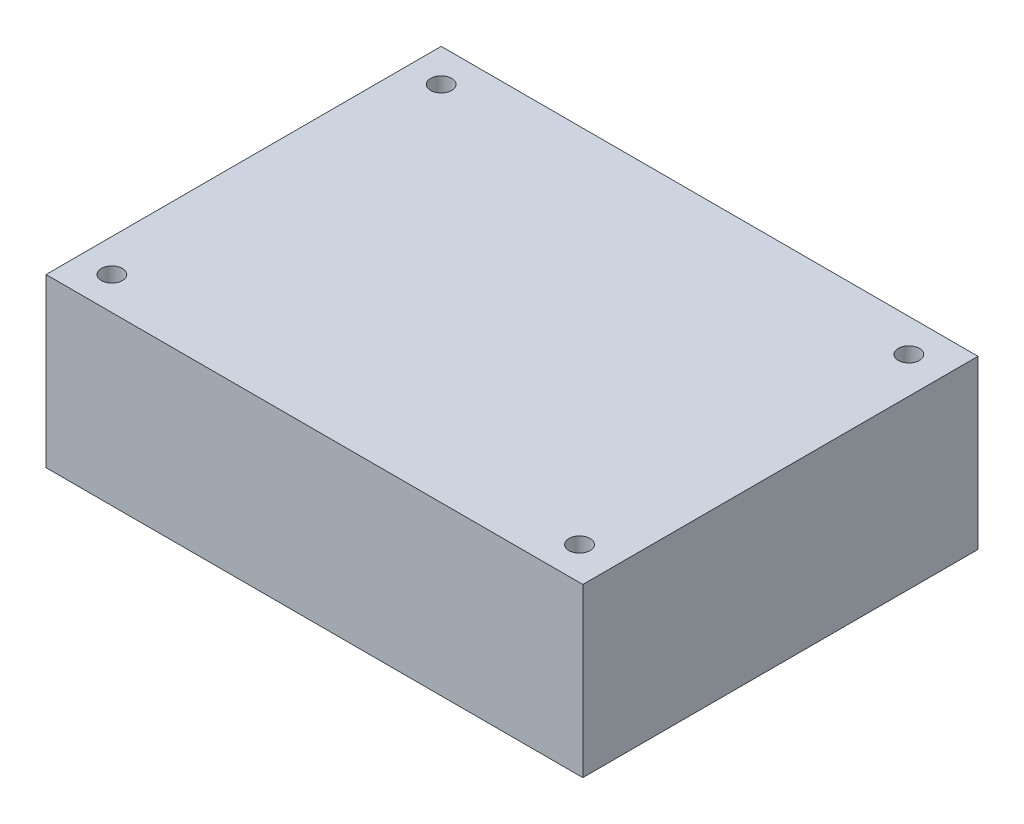
SolidWorks part; units mm, degrees
material "Default"
ref_plane "Front Plane" through (0, 0, 0) normal (0, 0, 1) x (1, 0, 0)
ref_plane "Top Plane" through (0, 0, 0) normal (0, 1, 0) x (1, 0, 0)
ref_plane "Right Plane" through (0, 0, 0) normal (1, 0, 0) x (0, 0, -1)
sketch "Sketch1" plane through (0, 0, 0) normal (0, 1, 0) x (1, 0, 0)
  line L1 (-40.75, 29.9999) -> (40.75, 29.9999)
  line L2 (-40.75, 29.9999) -> (-40.75, -29.9999)
  line L3 (-40.75, -29.9999) -> (40.75, -29.9999)
  line L4 (40.75, 29.9999) -> (40.75, -29.9999)
  point P4 (0, 29.9999)
  point P6 (-40.75, 0)
  dimension "D1" = 81.5
  dimension "D2" = 59.9999
extrude "Boss-Extrude1" add sketch "Sketch1" along normal blind 25.4
hole_wizard "3.2mm Mount holes" positions "Sketch2" profile "Sketch3" hole size "Ø3.0" standard "ANSI Metric" end condition through all
sketch "Sketch2" plane through (0, 25.4, 0) normal (0, 1, 0) x (1, 0, 0)
  line L0 (-40.75, 29.9999) -> (-40.75, -29.9999) construction
  line L1 (40.75, 29.9999) -> (-40.75, 29.9999) construction
  line L2 (-40.75, -29.9999) -> (40.75, -29.9999) construction
  point P0 (-35.75, 24.9999)
  point P2 (35.2501, -24.9999)
  point P4 (35.2501, 24.9999)
  point P6 (-35.75, -24.9999)
  dimension "D1" = 5
  dimension "D2" = 5
  dimension "D3" = 5
  dimension "D4" = 71.0001
sketch "Sketch3" plane through (-35.75, 25.4, -24.9999) normal (1, 0, 0) x (0, 0, 1)
  line L0 (0, 0) -> (0, 25.4)
  line L1 (0, 25.4) -> (1.6, 25.4)
  line L2 (1.6, 25.4) -> (1.6, 0)
  line L5 (1.6, 0) -> (0, 0)
  line L11 (0, -6.35) -> (0, 107.95) construction
  dimension "Thru Hole Dia." = 3.2
  dimension "Thru Hole Depth" = 25.4
